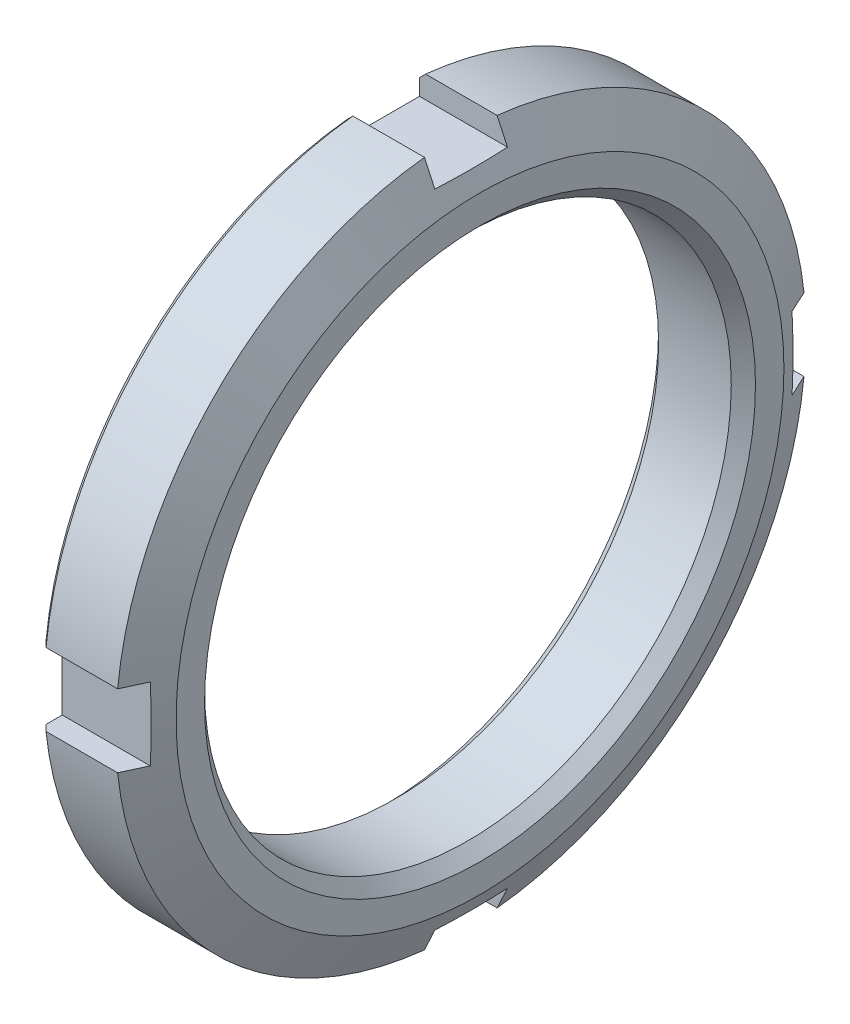
SolidWorks part; units mm, degrees
ref_plane "前视基准面" through (0, 0, 0) normal (0, 0, 1) x (1, 0, 0)
ref_plane "上视基准面" through (0, 0, 0) normal (0, 1, 0) x (1, 0, 0)
ref_plane "右视基准面" through (0, 0, 0) normal (1, 0, 0) x (0, 0, -1)
other "Configuration Table"
sketch "草图1" plane through (0, 0, 0) normal (1, 0, 0) x (0, 0, -1)
  circle A0 centre (0, 0) radius 21.75
  circle A1 centre (0, 0) radius 28.5
  dimension "D1" = 57
  dimension "D2" = 43.5
extrude "凸台-拉伸1" add sketch "草图1" along normal blind 8
chamfer "倒角1" distance 1 angle 45 2 edges at (0, 0, -21.75) (8, 0, -21.75)
chamfer "倒角2" distance 0.5 angle 45 1 edges at (0, 0, -28.5)
sketch "草图2" plane through (8, 0, 0) normal (1, 0, 0) x (0, 0, -1)
  line L0 (-3, 28.3417) -> (-3, 26.5)
  line L1 (-3, 26.5) -> (3, 26.5)
  line L2 (3, 26.5) -> (3, 28.3417)
  circle A0 centre (0, 0) radius 28.5 construction
  arc A2 (3, 28.3417) -> (-3, 28.3417) centre (0, 0) ccw
  point P4 (0, 26.5)
  point P6 (0, 0)
  dimension "D1" = 26.5
  dimension "D2" = 6
extrude "切除-拉伸1" cut sketch "草图2" against normal blind 8
pattern_circular "阵列(圆周)1" count 4 over 360 about axis through (0, 0, 0) along (1, 0, 0) of "切除-拉伸1"
sketch "草图3" plane through (0, 0, 0) normal (0, 0, 1) x (1, 0, 0)
  line L0 (3.2951, 35.1896) -> (8, 25.1)
  line L2 (8, 3) -> (8, 28.3417) construction
  line L3 (8, 25.1) -> (8, 35.1896)
  line L4 (8, 35.1896) -> (3.2951, 35.1896)
  point P7 (0, 0)
  dimension "D1" = 25
  dimension "D2" = 25.1
  dimension "D3" = 10.0896
revolve "切除-旋转1" cut sketch "草图3" angle 360 about axis through (8, 0, 0) along (-1, 0, 0)
